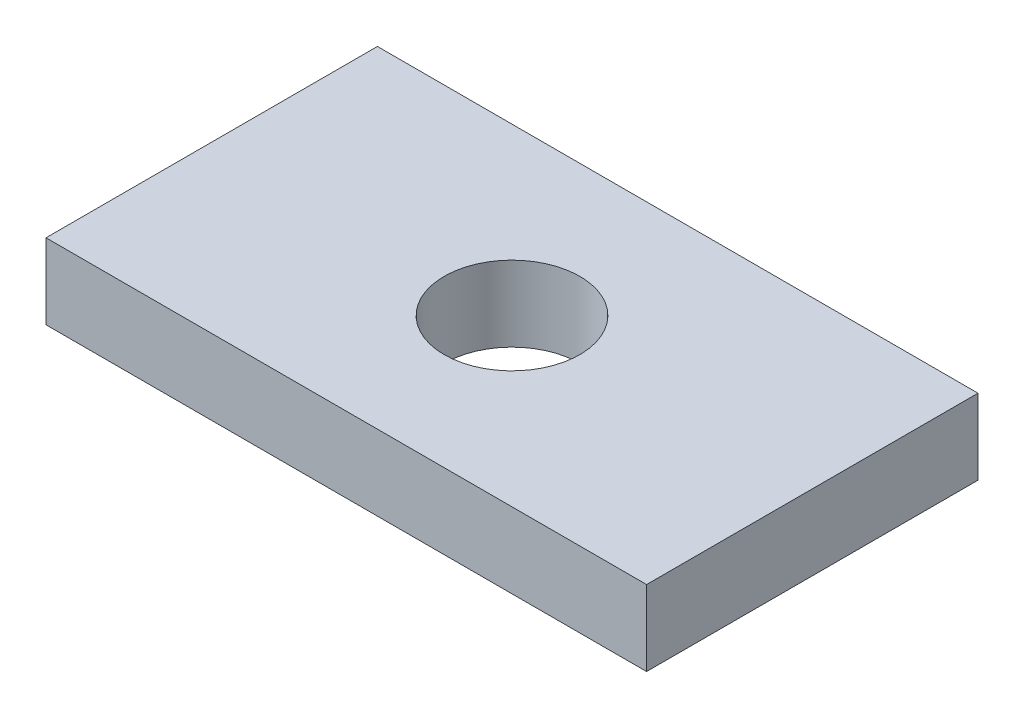
SolidWorks part; units mm, degrees
ref_plane "Спереди" through (0, 0, 0) normal (0, 0, 1) x (1, 0, 0)
ref_plane "Сверху" through (0, 0, 0) normal (0, 1, 0) x (1, 0, 0)
ref_plane "Справа" through (0, 0, 0) normal (1, 0, 0) x (0, 0, -1)
sketch "Эскиз1" plane through (0, 0, 0) normal (0, 1, 0) x (1, 0, 0)
  line L1 (0, 0) -> (79.6887, 0)
  line L2 (0, 0) -> (0, -43.9739)
  line L3 (0, -43.9739) -> (79.6887, -43.9739)
  line L4 (79.6887, 0) -> (79.6887, -43.9739)
extrude "Вытянуть1" add sketch "Эскиз1" along normal blind 10
sketch "Эскиз2" plane through (0, 10, 0) normal (0, 1, 0) x (1, 0, 0)
  circle A0 centre (39.8443, -21.987) radius 9
extrude "Вырез-Вытянуть1" cut sketch "Эскиз2" against normal through all
